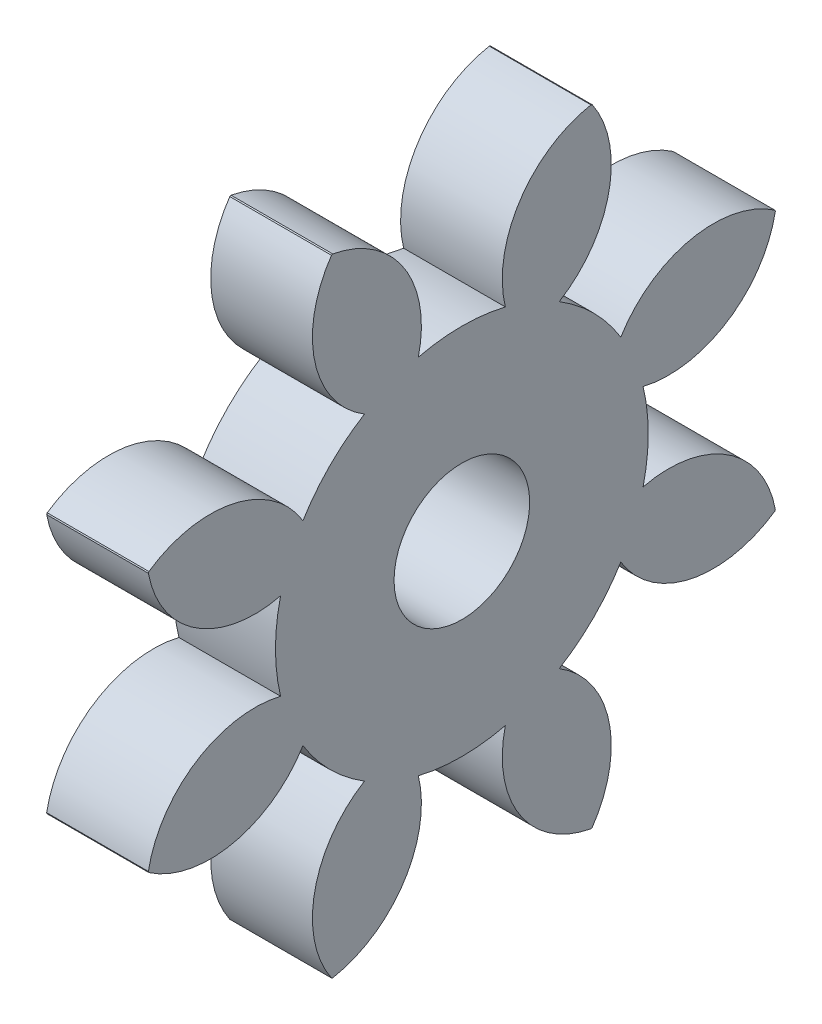
SolidWorks part; units mm, degrees
material "Zinc AC41A Alloy, As Cast"
ref_plane "Plane1" through (0, 0, 0) normal (0, 0, 1) x (1, 0, 0)
ref_plane "Plane2" through (0, 0, 0) normal (0, 1, 0) x (1, 0, 0)
ref_plane "Plane3" through (0, 0, 0) normal (1, 0, 0) x (0, 0, -1)
sketch "HoldingSke" plane through (0, 0, 0) normal (0, 1, 0) x (1, 0, 0)
  line L0 (0, 0) -> (0.9903, -0.1392)
  line L1 (-15, 0) -> (100, 0) construction
  line L2 (0, 0) -> (-2.1039, 2.3779)
  line L3 (0, 0) -> (-11.863, 4.5341)
  line L4 (0, 0) -> (8.552, 1.2019)
  line L5 (0, 0) -> (-46.8476, -17.4728)
  line L6 (0, 0) -> (-1.2434, -0.839)
  line L7 (-2.1039, 2.3779) -> (8.6586, 51.2059)
  line L8 (-76.2, 54.61) -> (-75.9, 54.61)
  line L9 (-71.009, 38.7566) -> (-53.1078, 45.2721)
  line L10 (-76.2, 71.12) -> (104.1128, 71.12)
  line L11 (0, 0) -> (-1.5, 0)
  line L12 (-76.2, 101.6) -> (-76.162, 101.6)
  line L13 (24.9733, 27.94) -> (52.9518, 28.4284)
  line L14 (24.9733, 27.94) -> (24.9743, 27.94)
  line L15 (24.9733, 27.94) -> (100.4006, 29.5858)
  line L16 (-63.627, -1) -> (-12.827, -1)
  circle A0 centre (0, 0) radius 1
  circle A1 centre (0, 0) radius 2.749
  circle A2 centre (0, 0) radius 37.5
  circle A3 centre (0, 0) radius 1
  dimension "MHD" = 5.498
  dimension "Hub_dia" = 75
  dimension "Bore" = 2
  dimension "MBD" = 2
  dimension "Num_teeth" = 8
  dimension "Pitch" = 1
  dimension "Overall_len" = 50
  dimension "Show_teeth" = 8
  dimension "Thickness" = 1.5
  dimension "OAL" = 50.0001
  dimension "T_dim" = 0.3
  dimension "Ap" = 20
  dimension "H" = 19.05
  dimension "Pitch_radius" = 180.3128
  dimension "Width" = 1.5
  dimension "Backlash" = 0.038
  dimension "Addendum_fac" = 1
  dimension "Dedendum_fac" = 1.25
  dimension "Clearance_fac" = 0.25
  dimension "Dedendum_add" = 0.001
  dimension "Module" = 1
sketch "BasProSke" plane through (0, 0, 0) normal (0, 1, 0) x (1, 0, 0)
  line L0 (-10, 0) -> (60, 0) construction
  line L1 (0, 0) -> (0, 5)
  line L2 (0, 0) -> (1.5, 0)
  line L3 (1.5, 0) -> (1.5, 5)
  line L4 (1.5, 5) -> (0, 5)
  dimension "Thickness" = 1.5
  dimension "Diameter" = 10
revolve "Base-Revolve" add sketch "BasProSke" angle 360 about L0
sketch "TooCutSke" plane through (0, 0, 0) normal (1, 0, 0) x (0, 0, -1)
  line L1 (0, 0) -> (0, 107) construction
  line L2 (0, 0) -> (-0.8466, 3.9094) construction
  line L3 (0, 0) -> (-3.0123, 7.2724) construction
  line L4 (-0.8466, 3.9094) -> (-1.5062, 3.6362) construction
  arc A0 (0.6415, 2.6731) -> (-0.6415, 2.6731) centre (0, 0) ccw
  arc A1 (1.9508, 4.6313) -> (-1.9508, 4.6313) centre (0, 0) ccw
  circle A2 centre (0, 0) radius 4 construction
  circle A3 centre (0, 0) radius 3.7588 construction
  arc A4 (-0.6415, 2.6731) -> (-1.9508, 4.6313) centre (-2.1964, 3.0503) ccw
  arc A5 (1.9508, 4.6313) -> (0.6415, 2.6731) centre (2.1964, 3.0503) ccw
  dimension "Root_dia" = 5.498
  dimension "Overcut_dia" = 10.0508
  dimension "Pitch_dia" = 8
  dimension "Base_dia" = 7.5175
  dimension "Flank_rad" = 1.6
  dimension "Half_ang" = 22.5
  dimension "Half_CT" = 0.7139
extrude "ToothCut" cut sketch "TooCutSke" along normal through all
fillet "Breaks" [suppressed] radius 0.02
fillet "RootFillets" [suppressed] radius 0.251
pattern_circular "TeethCuts" count 8 every 45 about axis through (-10, 0, 0) along (1, 0, 0) of "ToothCut", "RootFillets", "Breaks"
sketch "HubNeaOneSke" plane through (0, 0, 0) normal (-1, 0, 0) x (0, 0, 1)
  circle A0 centre (0, 0) radius 2.749
  dimension "Diameter" = 5.498
extrude "HubNearOne" [suppressed] add sketch "HubNeaOneSke" along normal blind 48.5001
sketch "HubNeaBotSke" plane through (0, 0, 0) normal (-1, 0, 0) x (0, 0, 1)
  circle A0 centre (0, 0) radius 2.749
  dimension "Diameter" = 5.498
extrude "HubNearBoth" [suppressed] add sketch "HubNeaBotSke" along normal blind 24.25
ref_plane "FarPln" through (1.5, 0, 0) normal (1, 0, 0) x (0, 0, -1)
sketch "HubFarSke" plane through (1.5, 0, 0) normal (1, 0, 0) x (0, 0, -1)
  circle A0 centre (0, 0) radius 2.749
  dimension "Diameter" = 5.498
extrude "HubFar" [suppressed] add sketch "HubFarSke" along normal blind 24.25
sketch "BorSke" plane through (0, 0, 0) normal (1, 0, 0) x (0, 0, -1)
  circle A0 centre (0, 0) radius 1
  dimension "Diameter" = 2
extrude "Bore" cut sketch "BorSke" along normal mid plane 100.0001
sketch "KeySke" plane through (0, 0, 0) normal (1, 0, 0) x (0, 0, -1)
  line L0 (-0.4, 0) -> (-0.4, 1.3)
  line L1 (-0.4, 1.3) -> (0.4, 1.3)
  line L2 (0.4, 1.3) -> (0.4, 0)
  line L3 (0, 0) -> (0, 34) construction
  line L4 (-0.4, 0) -> (0.4, 0)
  dimension "Offset" = 1.3
  dimension "Width" = 0.8
extrude "Keyway" [suppressed] cut sketch "KeySke" along normal mid plane 100.0001
pattern_circular "Keyway2" [suppressed] count 2 every 90 about axis through (-10, 0, 0) along (1, 0, 0)
equation "' \"Module@HoldingSke\" = 6.35"
equation "' \"Num_teeth@HoldingSke\" = 12"
equation "' \"Ap@HoldingSke\" =  20"
equation "' \"Ap@HoldingSke\" = 20"
equation "' \"Width@HoldingSke\" = 0.5 * 25.4"
equation "' \"Hub_dia@HoldingSke\"= 1 * 25.4"
equation "' \"Hub_dia@HoldingSke\" = 1 * 25.4"
equation "' \"Overall_len@HoldingSke\" = 1.0 * 25.4"
equation "' \"Bore@HoldingSke\" = 0.75 * 25.4"
equation "' \"T_dim@HoldingSke\" = 0.1 * 25.4"
equation "' \"Width@KeySke\" = 0.25 * 25.4"
equation "' \"Show_teeth@HoldingSke\" = 13"
equation "' \"Backlash@HoldingSke\" = 0.009 * 25.4"
equation "' \"Addendum_fac@HoldingSke\" = 1.0"
equation "' \"Dedendum_fac@HoldingSke\" = 1.25"
equation "' \"Dedendum_add@HoldingSke\" = 0.00005 * 25.4"
equation "' \"Clearance_fac@HoldingSke\" = 0.25"
equation "\"Pitch@HoldingSke\" = 1 / \"Module@HoldingSke\""
equation "\"Overcut_dia@TooCutSke\" = (\"Num_teeth@HoldingSke\" + 2 * \"Addendum_fac@HoldingSke\") / \"Pitch@HoldingSke\" + 0.002 * 25.4"
equation "\"Pitch_dia@TooCutSke\" = \"Num_teeth@HoldingSke\" / \"Pitch@HoldingSke\""
equation "\"Base_dia@TooCutSke\" = \"Num_teeth@HoldingSke\" / \"Pitch@HoldingSke\" * cos((\"Ap@HoldingSke\"  * 3.14159265 / 180))"
equation "\"Root_dia@TooCutSke\" = (\"Num_teeth@HoldingSke\" + 2) / \"Pitch@HoldingSke\" - 2 * (\"Addendum_fac@HoldingSke\" + \"Dedendum_fac@HoldingSke\") / \"Pitch@HoldingSke\" - \"Dedendum_add@HoldingSke\" * 2"
equation "\"Half_ang@TooCutSke\" = 180 / \"Num_teeth@HoldingSke\""
equation "\"Half_CT@TooCutSke\" = \"Num_teeth@HoldingSke\" / \"Pitch@HoldingSke\" * sin((3.14159265 / 2 / \"Num_teeth@HoldingSke\")) / 2 - 7 * \"Backlash@HoldingSke\" / 4"
equation "\"Flank_rad@TooCutSke\" = \"Num_teeth@HoldingSke\" / \"Pitch@HoldingSke\" / 5"
equation "\"Radius@RootFillets\" = \"Clearance_fac@HoldingSke\" / \"Pitch@HoldingSke\" + \"Dedendum_add@HoldingSke\""
equation "\"Break_rad@Breaks\" = 0.02 / \"Pitch@HoldingSke\""
equation "\"Thickness@HoldingSke\" = \"Width@HoldingSke\""
equation "\"OAL@HoldingSke\" = \"Thickness@HoldingSke\""
equation "\"MHD@HoldingSke\" = (\"Num_teeth@HoldingSke\" + 2) / \"Pitch@HoldingSke\" - 2 * (\"Addendum_fac@HoldingSke\" + \"Dedendum_fac@HoldingSke\")  / \"Pitch@HoldingSke\" - \"Dedendum_add@HoldingSke\" * 2"
equation "\"MBD@HoldingSke\" = (\"Num_teeth@HoldingSke\" + 2) / \"Pitch@HoldingSke\" - 2 * (\"Addendum_fac@HoldingSke\" + \"Dedendum_fac@HoldingSke\")  / \"Pitch@HoldingSke\" - \"Dedendum_add@HoldingSke\" * 2 - 0.002 * 25.4"
equation "\"MHD@HoldingSke\" = ((sgn( \"MHD@HoldingSke\" - \"Hub_dia@HoldingSke\" )-1)*( \"MHD@HoldingSke\" - \"Hub_dia@HoldingSke\" ))/-2+ \"Hub_dia@HoldingSke\""
equation "\"MBD@HoldingSke\" = ((sgn( \"MBD@HoldingSke\" - \"Bore@HoldingSke\" )-1)*( \"MBD@HoldingSke\" - \"Bore@HoldingSke\" ))/-2+ \"Bore@HoldingSke\""
equation "\"OAL@HoldingSke\" = ((sgn( \"OAL@HoldingSke\" - \"Overall_len@HoldingSke\" )+1)*( \"OAL@HoldingSke\" - \"Overall_len@HoldingSke\" ))/2 + \"Overall_len@HoldingSke\" + 0.000002 * 25.4"
equation "\"Num_teeth@TeethCuts\" = int( \"Show_teeth@HoldingSke\" ) + 1"
equation "\"Num_teeth@TeethCuts\" = ((sgn( \"Num_teeth@TeethCuts\" - \"Num_teeth@HoldingSke\" )-1)*( \"Num_teeth@TeethCuts\" - \"Num_teeth@HoldingSke\" ))/-2+ \"Num_teeth@HoldingSke\""
equation "\"Num_teeth@TeethCuts\" = ((sgn( \"Num_teeth@TeethCuts\" - 2.0)+1)*( \"Num_teeth@TeethCuts\" - 2.0))/2 +2.0"
equation "\"Angle@TeethCuts\" = 360.0 / \"Num_teeth@HoldingSke\""
equation "\"Diameter@BasProSke\" = (\"Num_teeth@HoldingSke\" + 2 * \"Addendum_fac@HoldingSke\") / \"Pitch@HoldingSke\""
equation "\"Thickness@BasProSke\"  = \"Thickness@HoldingSke\""
equation "' \"Fillet_rad@BasProSke\" =  \"Thickness@HoldingSke\" * 0.05"
equation "' \"Fillet_rad@BasProSke\" = \"Thickness@HoldingSke\" * 0.05"
equation "\"MHD@HoldingSke\" = ((sgn( \"MHD@HoldingSke\" - \"Root_dia@TooCutSke\" )-1)*( \"MHD@HoldingSke\" - \"Root_dia@TooCutSke\" ))/-2+ \"Root_dia@TooCutSke\""
equation "\"Diameter@HubNeaOneSke\" = \"MHD@HoldingSke\""
equation "\"Length@HubNearOne\" = \"OAL@HoldingSke\" - \"Thickness@BasProSke\""
equation "\"Diameter@HubNeaBotSke\" = \"MHD@HoldingSke\""
equation "\"Length@HubNearBoth\" = ( \"OAL@HoldingSke\" - \"Thickness@BasProSke\" ) / 2.0"
equation "\"Thickness@FarPln\" = \"Thickness@BasProSke\""
equation "\"Diameter@HubFarSke\" = \"MHD@HoldingSke\""
equation "\"Length@HubFar\" = ( \"OAL@HoldingSke\" - \"Thickness@BasProSke\" ) / 2.0"
equation "\"Diameter@BorSke\" = \"MBD@HoldingSke\""
equation "\"D1@Bore\" = \"OAL@HoldingSke\" * 2.0"
equation "\"D1@Keyway\" = \"OAL@HoldingSke\" * 2.0"
equation "\"Offset@KeySke\" = \"T_dim@HoldingSke\" + \"MBD@HoldingSke\" / 2.0"
